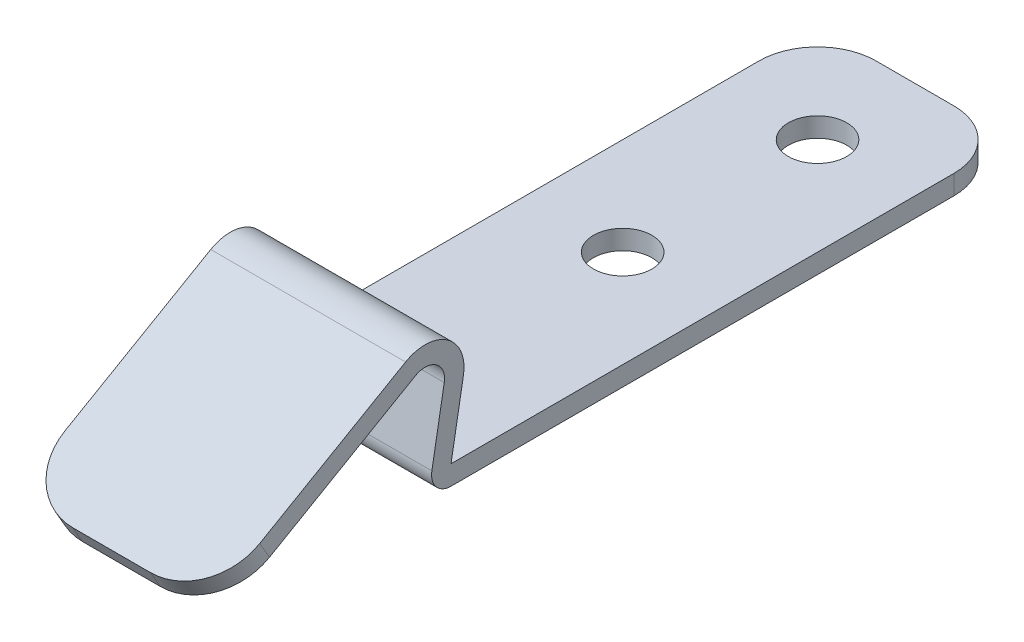
SolidWorks part; units mm, degrees
material "Plain Carbon Steel"
ref_plane "Front Plane" through (0, 0, 0) normal (0, 0, 1) x (1, 0, 0)
ref_plane "Top Plane" through (0, 0, 0) normal (0, 1, 0) x (1, 0, 0)
ref_plane "Right Plane" through (0, 0, 0) normal (1, 0, 0) x (0, 0, -1)
sketch "Sketch1" plane through (0, 0, 0) normal (1, 0, 0) x (0, 0, -1)
  line L0 (0, 0) -> (-28.8082, 0)
  line L1 (-29.7931, 1.1736) -> (-29.1569, 4.7817)
  line L2 (-30.6417, 5.8214) -> (-40.7246, 0)
  arc A0 (-28.8082, 0) -> (-29.7931, 1.1736) centre (-28.8082, 1) cw
  arc A1 (-29.1569, 4.7817) -> (-30.6417, 5.8214) centre (-30.1417, 4.9554) ccw
  point P7 (-30, 0)
  point P10 (-28.7845, 6.8937)
  dimension "D4" = 1
  dimension "D1" = 30
  dimension "D2" = 7
  dimension "D3" = 30
  dimension "D5" = 80
extrude "Extrude-Thin1" add sketch "Sketch1" along normal mid plane 10 thin
fillet "Fillet1" radius 3 4 edges at (-5, 0.433, 40.9746) (5, 0.433, 40.9746) (5, 0.5, 0) (-5, 0.5, 0)
sketch "Sketch2" plane through (0, 1, 0) normal (0, 1, 0) x (1, 0, 0)
  line L0 (0, 0) -> (0, -5) construction
  line L1 (0, -5) -> (0, -15) construction
  circle A0 centre (0, -5) radius 1.5
  circle A1 centre (0, -15) radius 1.5
  dimension "D3" = 3
  dimension "D1" = 5
  dimension "D2" = 10
extrude "Cut-Extrude1" cut sketch "Sketch2" against normal blind 10
